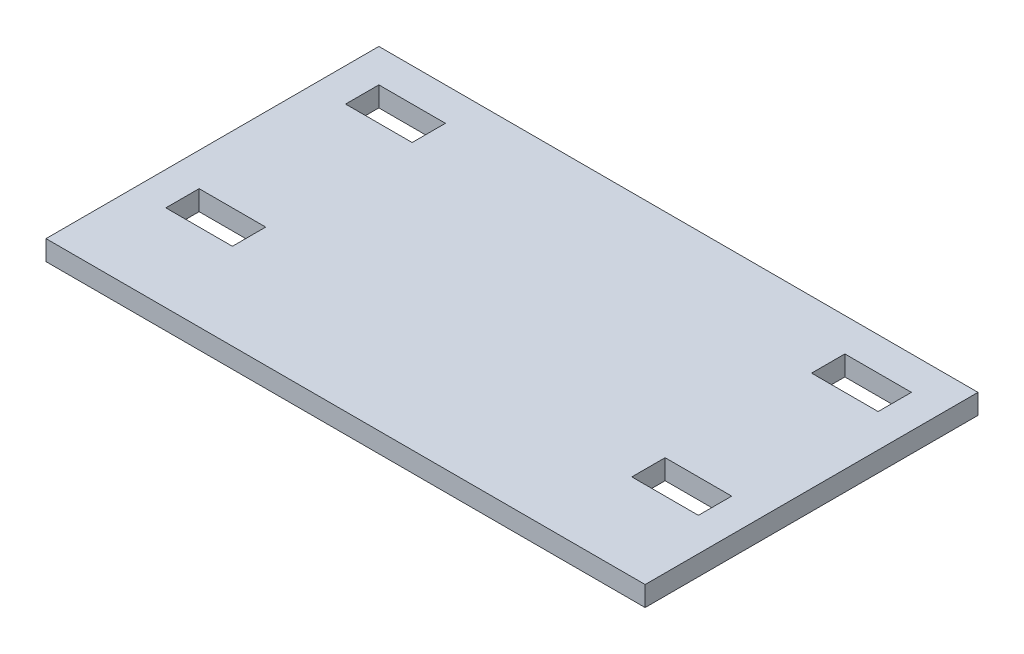
SolidWorks part; units mm, degrees
ref_plane "Front Plane" through (0, 0, 0) normal (0, 0, 1) x (1, 0, 0)
ref_plane "Top Plane" through (0, 0, 0) normal (0, 1, 0) x (1, 0, 0)
ref_plane "Right Plane" through (0, 0, 0) normal (1, 0, 0) x (0, 0, -1)
sketch "Sketch1" plane through (0, 0, 0) normal (0, 1, 0) x (1, 0, 0)
  line L1 (-45, -25) -> (45, -25)
  line L2 (-45, -25) -> (-45, 25)
  line L3 (-45, 25) -> (45, 25)
  line L4 (45, -25) -> (45, 25)
  line L5 (-45, -25) -> (45, 25) construction
  line L6 (-45, 25) -> (45, -25) construction
  point P0 (0, 0)
  dimension "D1" = 90
  dimension "D2" = 50
extrude "Boss-Extrude1" add sketch "Sketch1" along normal blind 3 contours L3 L4 L1 L2
sketch "Sketch2" plane through (0, 3, 0) normal (0, 1, 0) x (1, 0, 0)
  line L0 (30, 4) -> (-30, 4) construction
  line L1 (-40, 20) -> (-30, 20)
  line L2 (-40, 20) -> (-40, 15)
  line L3 (-40, 15) -> (-30, 15)
  line L4 (-30, 20) -> (-30, 15)
  line L5 (0, 0) -> (0, 20.2665) construction
  line L6 (30, 20) -> (30, 15)
  line L7 (40, 15) -> (30, 15)
  line L8 (40, 20) -> (40, 15)
  line L9 (40, 20) -> (30, 20)
  line L10 (-45, 25) -> (45, 25) construction
  line L11 (40, -12) -> (30, -12)
  line L12 (40, -12) -> (40, -7)
  line L13 (40, -7) -> (30, -7)
  line L14 (30, -12) -> (30, -7)
  line L15 (-30, -12) -> (-30, -7)
  line L16 (-40, -7) -> (-30, -7)
  line L17 (-40, -12) -> (-40, -7)
  line L18 (-40, -12) -> (-30, -12)
  point P7 (0, 4)
  dimension "D1" = 10
  dimension "D2" = 60
  dimension "D3" = 5
  dimension "D4" = 5
  dimension "D5" = 16
extrude "Cut-Extrude1" cut sketch "Sketch2" along direction (0, -1, 0) on the side against the normal up to next (3 mm away)
